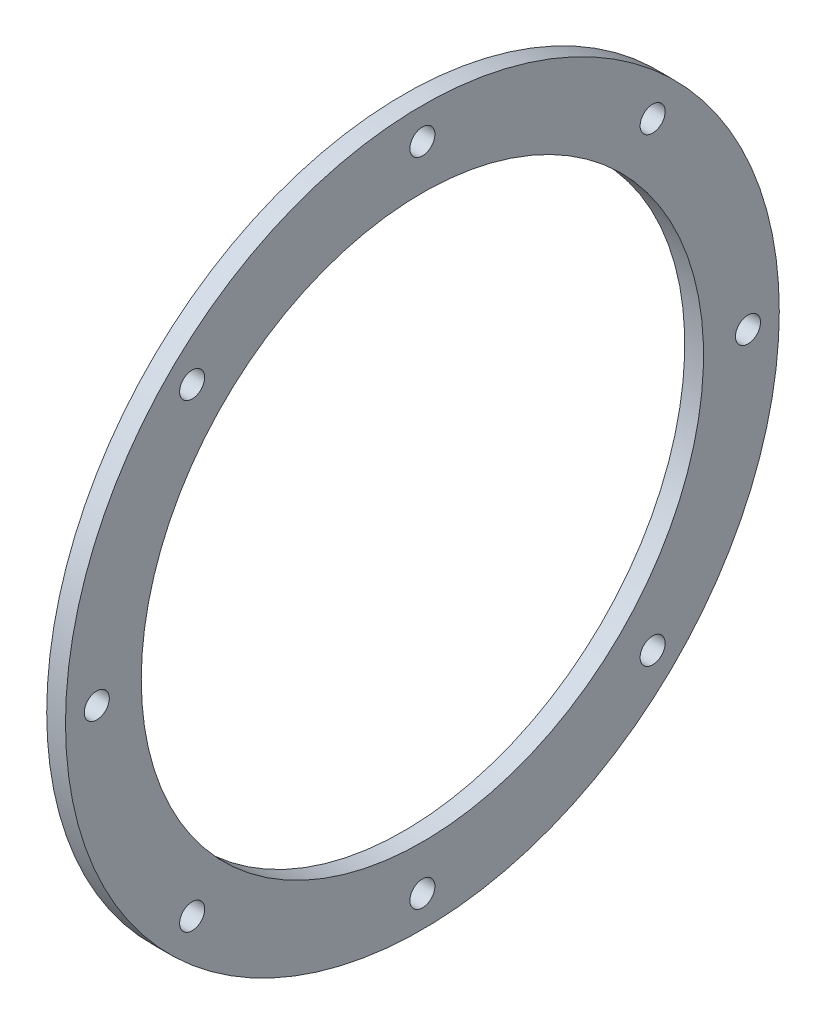
SolidWorks part; units mm, degrees
material "201 Annealed Stainless Steel (SS)"
ref_plane "Front Plane" through (0, 0, 0) normal (0, 0, 1) x (1, 0, 0)
ref_plane "Top Plane" through (0, 0, 0) normal (0, 1, 0) x (1, 0, 0)
ref_plane "Right Plane" through (0, 0, 0) normal (1, 0, 0) x (0, 0, -1)
sketch "Sketch2" plane through (0, 0, 0) normal (0, 0, 1) x (1, 0, 0)
  line L0 (-478.1119, 0) -> (17585.1179, 0) construction
  line L3 (9.2498, 44.9) -> (12.2498, 44.9)
  line L9 (9.2498, 57) -> (12.2498, 57)
  line L10 (9.2498, 57) -> (9.2498, 44.9)
  line L11 (9.2498, 44.9) -> (12.2498, 44.9)
  line L12 (12.2498, 57) -> (12.2498, 44.9)
  point P1 (10.7498, 57)
  dimension "D1" = 44.9
  dimension "D2" = 57
  dimension "D8" = 3
revolve "Revolve1" add sketch "Sketch2" angle 360 about L0
sketch "Sketch3" plane through (9.2498, 0, 0) normal (-1, 0, 0) x (0, 0, 1)
  circle A2 centre (0, 52) radius 2
  point P4 (0, 0)
  point P8 (-15.8546, 57.1409)
  point P9 (0, 0)
  dimension "D1" = 4
  dimension "D2" = 52
extrude "Cut-Extrude1" cut sketch "Sketch3" against normal blind 10
pattern_circular "CirPattern1" count 8 over 360 about axis through (0, 0, 0) along (1, 0, 0) of "Cut-Extrude1"
